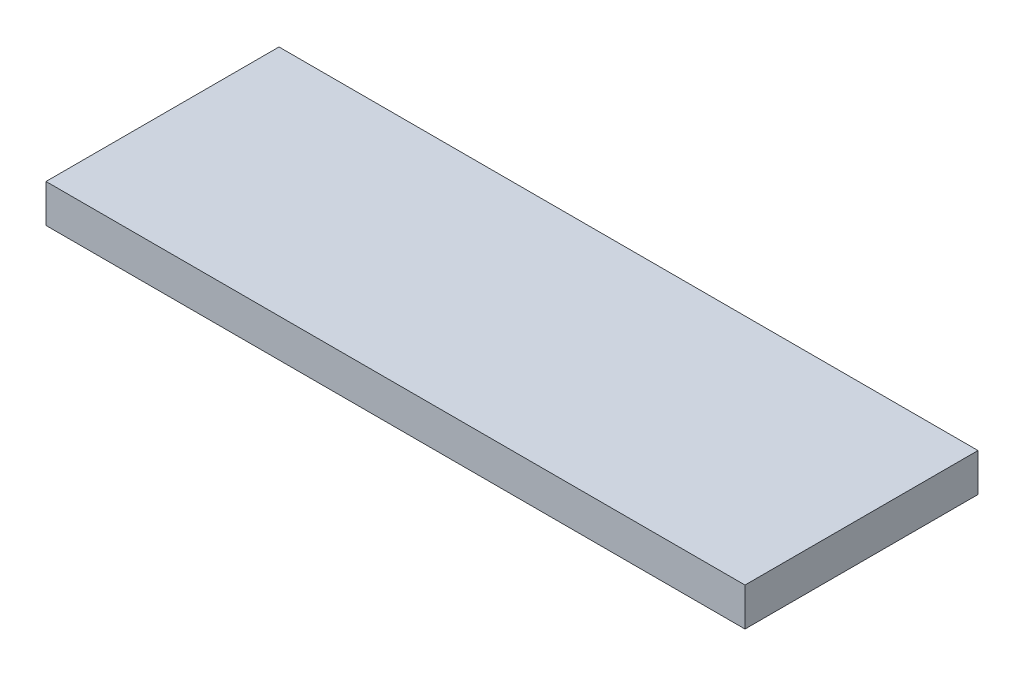
SolidWorks part; units mm, degrees
material "ABS"
ref_plane "Płaszczyzna przednia" through (0, 0, 0) normal (0, 0, 1) x (1, 0, 0)
ref_plane "Płaszczyzna górna" through (0, 0, 0) normal (0, 1, 0) x (1, 0, 0)
ref_plane "Płaszczyzna prawa" through (0, 0, 0) normal (1, 0, 0) x (0, 0, -1)
sketch "Szkic1" plane through (0, 0, 0) normal (0, 1, 0) x (1, 0, 0)
  line L1 (-82.5, 27.5) -> (82.5, 27.5)
  line L2 (-82.5, 27.5) -> (-82.5, -27.5)
  line L3 (-82.5, -27.5) -> (82.5, -27.5)
  line L4 (82.5, 27.5) -> (82.5, -27.5)
  line L5 (-82.5, 27.5) -> (82.5, -27.5) construction
  line L6 (-82.5, -27.5) -> (82.5, 27.5) construction
  point P0 (0, 0)
  dimension "D1" = 165
  dimension "D2" = 55
extrude "Dodanie-wyciągnięcie1" add sketch "Szkic1" along normal blind 9
